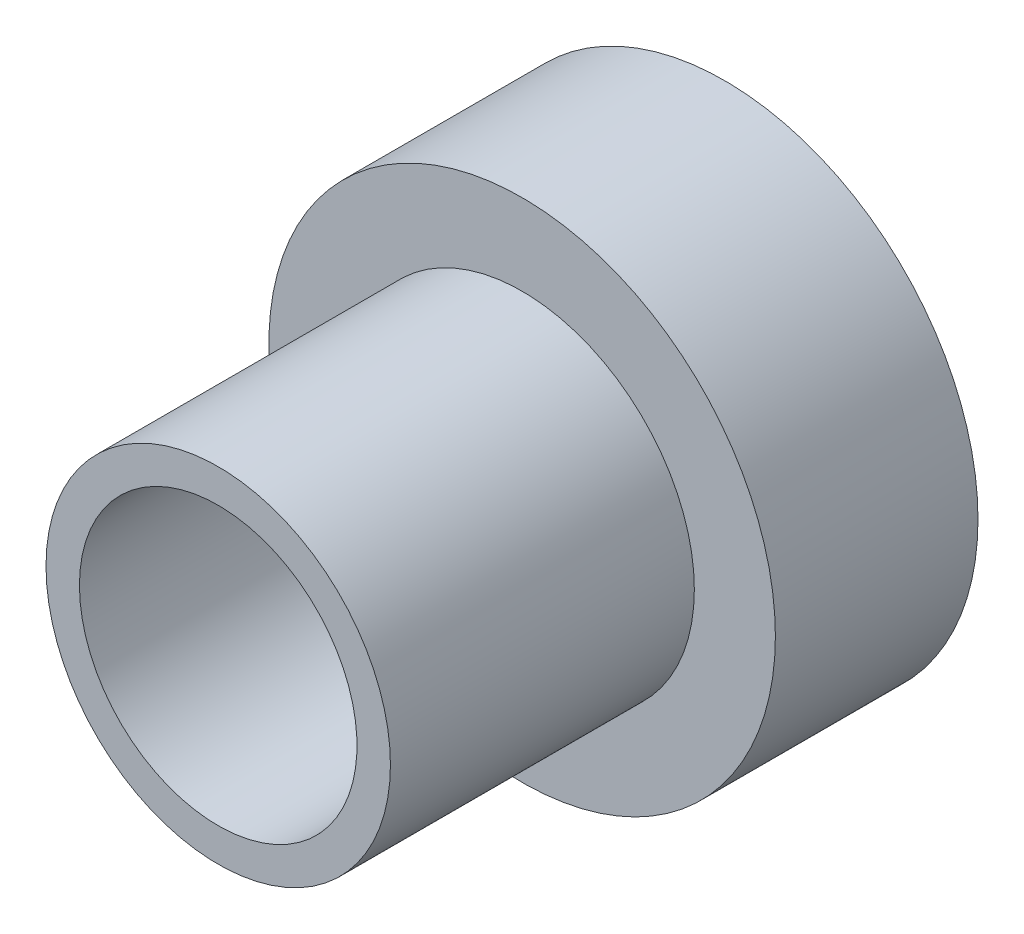
SolidWorks part; units mm, degrees
material "AISI 316  (SS)"
ref_plane "Front" through (0, 0, 0) normal (0, 0, 1) x (1, 0, 0)
ref_plane "Top" through (0, 0, 0) normal (0, 1, 0) x (1, 0, 0)
ref_plane "Right" through (0, 0, 0) normal (1, 0, 0) x (0, 0, -1)
sketch "Sketch1" plane through (0, 0, 0) normal (0, 0, 1) x (1, 0, 0)
  circle A0 centre (0, 0) radius 12.5
  dimension "D1" = 25
extrude "Boss-Extrude1" add sketch "Sketch1" along normal mid plane 25
sketch "Sketch2" plane through (0, 0, -12.5) normal (0, 0, -1) x (-1, 0, 0)
  circle A0 centre (0, 0) radius 6.85
  dimension "D1" = 13.7
extrude "Cut-Extrude1" cut sketch "Sketch2" against normal blind 25
sketch "Sketch3" plane through (0, 0, 12.5) normal (0, 0, 1) x (1, 0, 0)
  circle A0 centre (0, 0) radius 8.5
  dimension "D1" = 17
extrude "Cut-Extrude2" cut sketch "Sketch3" against normal blind 15 flip side to cut
